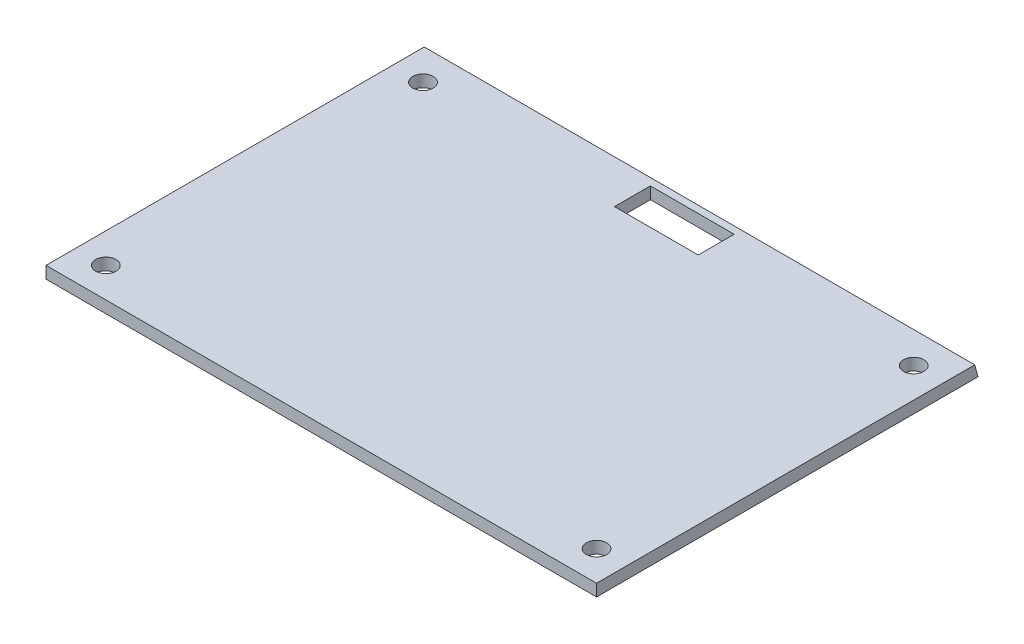
SolidWorks part; units mm, degrees
ref_plane "Спереди" through (0, 0, 0) normal (0, 0, 1) x (1, 0, 0)
ref_plane "Сверху" through (0, 0, 0) normal (0, 1, 0) x (1, 0, 0)
ref_plane "Справа" through (0, 0, 0) normal (1, 0, 0) x (0, 0, -1)
other "Configuration Table"
ref_plane "Плоскость1" through (0, 0, 55) normal (0, 0, 1) x (1, 0, 0)
sketch "Эскиз1" plane through (0, 0, 55) normal (0, 0, 1) x (1, 0, 0)
  line L1 (-46, -46) -> (46, -46)
  line L2 (-46, -46) -> (-46, -44)
  line L3 (-46, -44) -> (46, -44)
  line L4 (46, -46) -> (46, -44)
extrude "Rear_cover_2mm_1" add sketch "Эскиз1" along normal blind 65
ref_plane "Плоскость2" through (0, -47, 0) normal (0, 1, 0) x (1, 0, 0)
sketch "Эскиз2" plane through (0, -47, 0) normal (0, 1, 0) x (1, 0, 0)
  circle A0 centre (-41, -58) radius 1.7
  circle A1 centre (41, -58) radius 1.7
  circle A2 centre (-41, -115) radius 1.7
  circle A3 centre (41, -115) radius 1.7
ref_plane "Плоскость3" through (0, -47, 0) normal (0, 1, 0) x (1, 0, 0)
sketch "Эскиз3" plane through (0, -47, 0) normal (0, 1, 0) x (1, 0, 0)
  line L1 (-7, -58) -> (7, -58)
  line L2 (-7, -58) -> (-7, -64)
  line L3 (-7, -64) -> (7, -64)
  line L4 (7, -58) -> (7, -64)
extrude "Display_wire_exit_14x6_3" cut sketch "Эскиз3" along normal blind 4
ref_plane "Плоскость4" through (-47, 0, 0) normal (1, 0, 0) x (0, 0, -1)
sketch "Эскиз4" plane through (-47, 0, 0) normal (1, 0, 0) x (0, 0, -1)
  line L0 (-10, -47) -> (-10, -40)
  line L1 (-10, -40) -> (-57.8613, -40)
  line L2 (-57.8613, -40) -> (-55.9856, -47)
  line L3 (-55.9856, -47) -> (-10, -47)
extrude "Rear_cover_cage_roof_clearance_207" cut sketch "Эскиз4" along normal blind 94
ref_plane "Плоскость5" through (0, -47, 0) normal (0, 1, 0) x (1, 0, 0)
sketch "Эскиз5" plane through (0, -47, 0) normal (0, 1, 0) x (1, 0, 0)
  circle A0 centre (-41, -62) radius 1.7
  circle A1 centre (41, -62) radius 1.7
  circle A2 centre (-41, -115) radius 1.7
  circle A3 centre (41, -115) radius 1.7
extrude "Rear_cover_M3_clearance_final_208" cut sketch "Эскиз5" along normal blind 4
